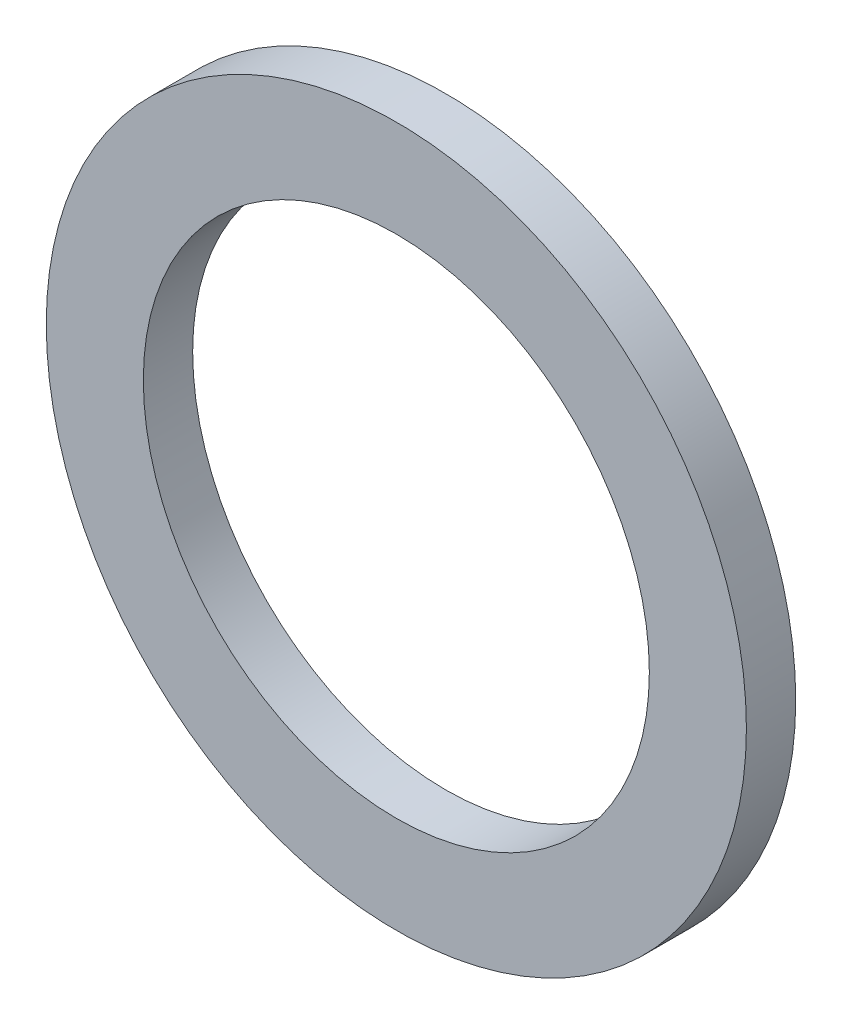
SolidWorks part; units mm, degrees
ref_plane "Front"
ref_plane "Top" through (0, 0, 0) normal (0, 1, 0) x (1, 0, 0)
ref_plane "Right" through (0, 0, 0) normal (1, 0, 0) x (0, 0, -1)
sketch "Sketch1" plane through (0, 0, 0) normal (0, 0, 1) x (1, 0, 0)
  circle A0 centre (0, 0) radius 4.0386
  circle A1 centre (0, 0) radius 5.588
  dimension "D1" = 8.0772
  dimension "D2" = 11.176
extrude "Extrude1" add sketch "Sketch1" along normal blind 0.7874
